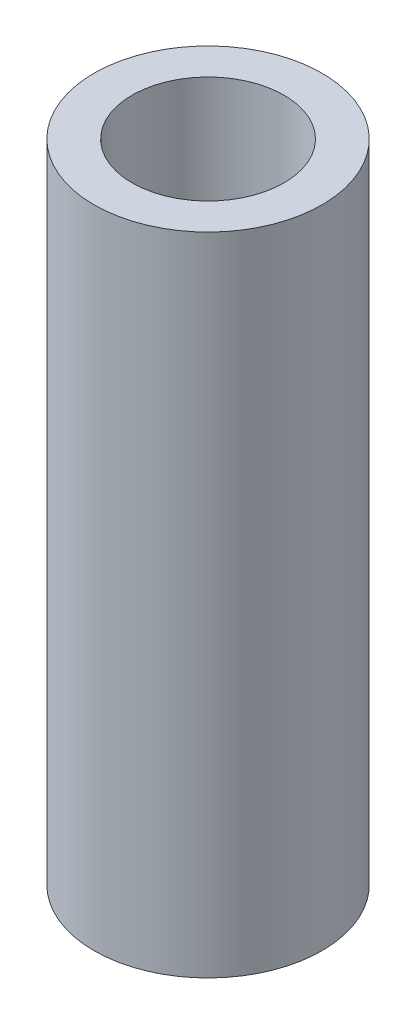
SolidWorks part; units mm, degrees
ref_plane "前视基准面" through (0, 0, 0) normal (0, 0, 1) x (1, 0, 0)
ref_plane "上视基准面" through (0, 0, 0) normal (0, 1, 0) x (1, 0, 0)
ref_plane "右视基准面" through (0, 0, 0) normal (1, 0, 0) x (0, 0, -1)
other "Configuration Table"
sketch "草图1" plane through (0, 0, 0) normal (0, 1, 0) x (1, 0, 0)
  circle A0 centre (0, 0) radius 5
  circle A1 centre (0, 0) radius 7.5
  dimension "D1" = 10
  dimension "D2" = 15
extrude "凸台-拉伸1" add sketch "草图1" along normal blind 42.5
